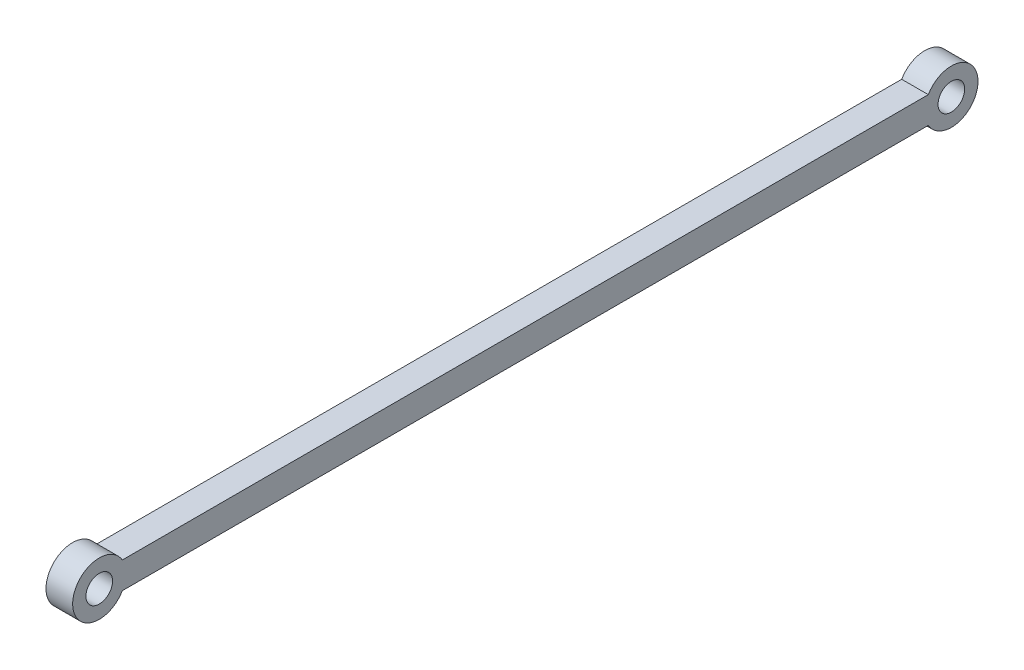
SolidWorks part; units mm, degrees
ref_plane "정면" through (0, 0, 0) normal (0, 0, 1) x (1, 0, 0)
ref_plane "윗면" through (0, 0, 0) normal (0, 1, 0) x (1, 0, 0)
ref_plane "우측면" through (0, 0, 0) normal (1, 0, 0) x (0, 0, -1)
sketch "스케치1" plane through (0, 0, 0) normal (1, 0, 0) x (0, 0, -1)
  line L0 (-40, 0) -> (40, 0) construction
  line L1 (-37.8349, 1.25) -> (37.8349, 1.25)
  line L3 (-37.8349, -1.25) -> (37.8349, -1.25)
  line L5 (0, 1.25) -> (0, -1.25) construction
  arc A0 (-37.8349, 1.25) -> (-37.8349, -1.25) centre (-40, 0) ccw
  circle A1 centre (-40, 0) radius 1.25
  arc A2 (37.8349, -1.25) -> (37.8349, 1.25) centre (40, 0) ccw
  circle A3 centre (40, 0) radius 1.25
  dimension "D3" = 5
  dimension "D4" = 5
  dimension "D1" = 2.5
  dimension "D2" = 80
extrude "보스-돌출1" add sketch "스케치1" along normal blind 2.5
equation "\"link11\" = 80"
equation "\"link12\" = 40"
equation "\"link21\"= 60"
equation "\"link22\"= 40"
equation "\"link31\"= 50"
equation "\"link32\"= 40"
equation "\"link41\"= 40"
equation "\"link42\"= 40"
equation "\"D2@스케치1\"=\"link11\""
